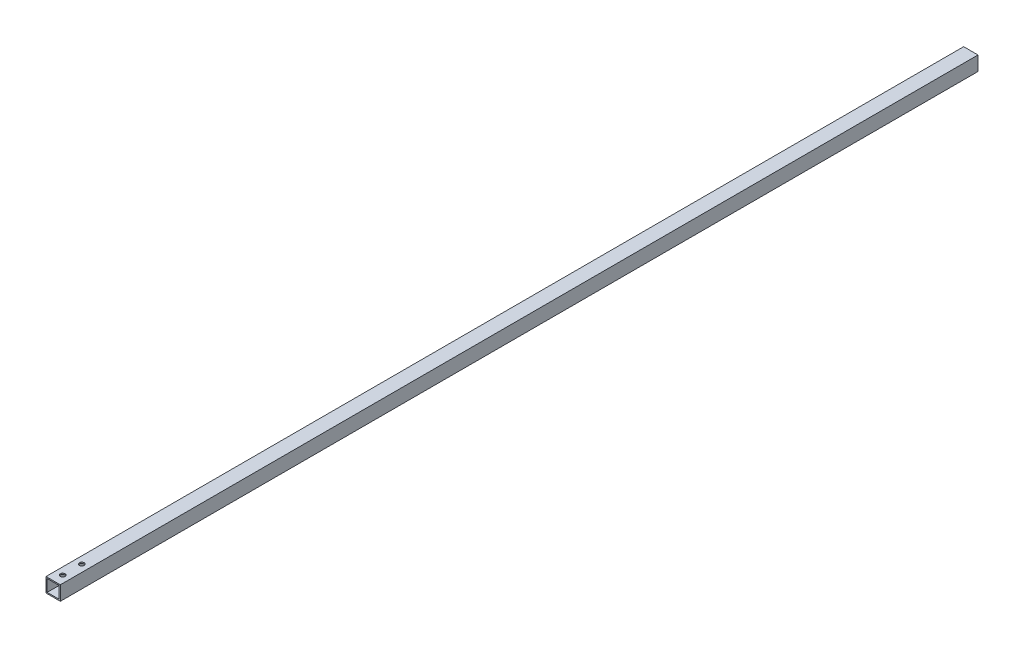
SolidWorks part; units mm, degrees
material "6061 Alloy"
ref_plane "Front Plane" through (0, 0, 0) normal (0, 0, 1) x (1, 0, 0)
ref_plane "Top Plane" through (0, 0, 0) normal (0, 1, 0) x (1, 0, 0)
ref_plane "Right Plane" through (0, 0, 0) normal (1, 0, 0) x (0, 0, -1)
sketch "Sketch1" plane through (0, 0, 0) normal (0, 0, 1) x (1, 0, 0)
  line L1 (-9.525, -9.525) -> (9.525, -9.525)
  line L2 (-9.525, -9.525) -> (-9.525, 9.525)
  line L3 (-9.525, 9.525) -> (9.525, 9.525)
  line L4 (9.525, -9.525) -> (9.525, 9.525)
  line L5 (-9.525, -9.525) -> (9.525, 9.525) construction
  line L6 (-9.525, 9.525) -> (9.525, -9.525) construction
  line L7 (-7.9375, -7.9375) -> (7.9375, -7.9375)
  line L8 (-7.9375, -7.9375) -> (-7.9375, 7.9375)
  line L9 (-7.9375, 7.9375) -> (7.9375, 7.9375)
  line L10 (7.9375, -7.9375) -> (7.9375, 7.9375)
  line L11 (-7.9375, -7.9375) -> (7.9375, 7.9375) construction
  line L12 (-7.9375, 7.9375) -> (7.9375, -7.9375) construction
  point P0 (0, 0)
  point P6 (0, 0)
  dimension "D1" = 19.05
  dimension "D2" = 19.05
  dimension "D3" = 1.5875
  dimension "D4" = 1.5875
extrude "Boss-Extrude1" add sketch "Sketch1" along normal mid plane 1219.2
sketch "Sketch2" plane through (0, 0, 0) normal (0, 1, 0) x (1, 0, 0)
  line L0 (0, -609.6) -> (0, -596.9) construction
  line L1 (9.525, -609.6) -> (-9.525, -609.6) construction
  line L2 (0, -609.6) -> (0, -571.5) construction
  circle A0 centre (0, -596.9) radius 3.175
  circle A1 centre (0, -571.5) radius 3.175
  point P8 (0, -294.3293)
  point P9 (0, -316.6474)
extrude "Cut-Extrude1" cut sketch "Sketch2" against normal through all both and the other way through all
